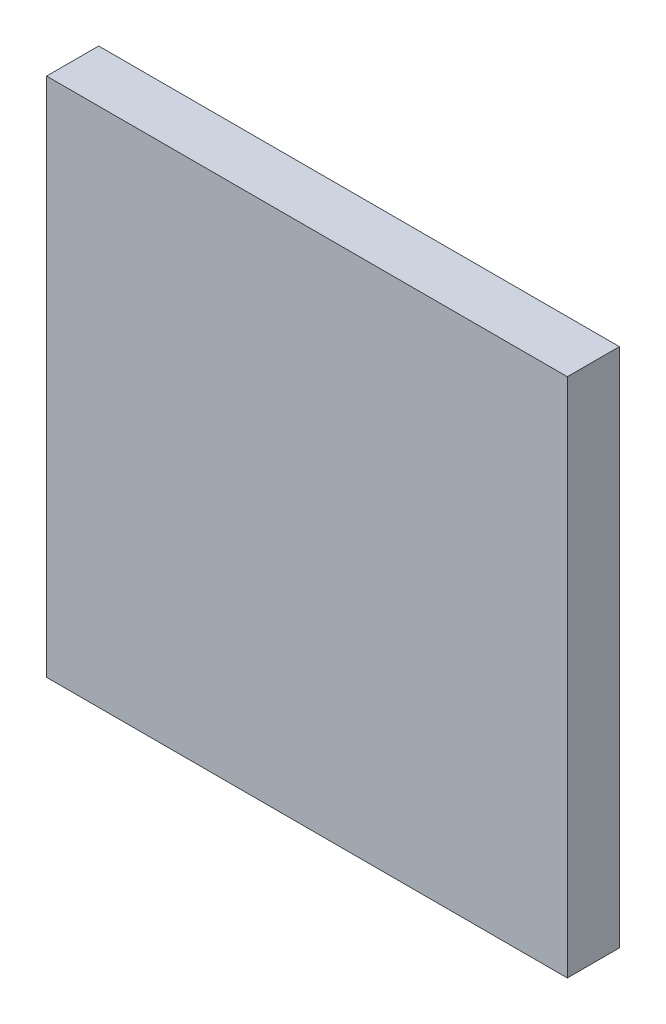
SolidWorks part; units mm, degrees
material "Дуб"
ref_plane "Спереди" through (0, 0, 0) normal (0, 0, 1) x (1, 0, 0)
ref_plane "Сверху" through (0, 0, 0) normal (0, 1, 0) x (1, 0, 0)
ref_plane "Справа" through (0, 0, 0) normal (1, 0, 0) x (0, 0, -1)
sketch "Эскиз стола" plane through (0, 0, 0) normal (0, 0, 1) x (1, 0, 0)
  line L1 (-250, 250) -> (250, 250)
  line L2 (-250, 250) -> (-250, -250)
  line L3 (-250, -250) -> (250, -250)
  line L4 (250, 250) -> (250, -250)
  line L5 (-250, 250) -> (250, -250) construction
  line L6 (-250, -250) -> (250, 250) construction
  line L14 (-200, 200) -> (200, 200)
  line L15 (200, 200) -> (200, -200)
  line L16 (-200, -200) -> (200, -200)
  line L17 (-200, 200) -> (-200, -200)
  line L18 (-150, 150) -> (150, 150)
  line L19 (150, 150) -> (150, -150)
  line L20 (-150, -150) -> (150, -150)
  line L21 (-150, 150) -> (-150, -150)
  line L22 (-100, 100) -> (100, 100)
  line L23 (100, 100) -> (100, -100)
  line L24 (-100, -100) -> (100, -100)
  line L25 (-100, 100) -> (-100, -100)
  line L26 (-50, 50) -> (50, 50)
  line L27 (50, 50) -> (50, -50)
  line L28 (-50, -50) -> (50, -50)
  line L29 (-50, 50) -> (-50, -50)
  point P0 (0, 0)
  dimension "D1" = 500
  dimension "D2" = 500
  dimension "D3" = 50
  dimension "D4" = 50
  dimension "D5" = 50
  dimension "D6" = 50
extrude "Стол" add sketch "Эскиз стола" against normal blind 50 contours L1 L4 L3 L2
